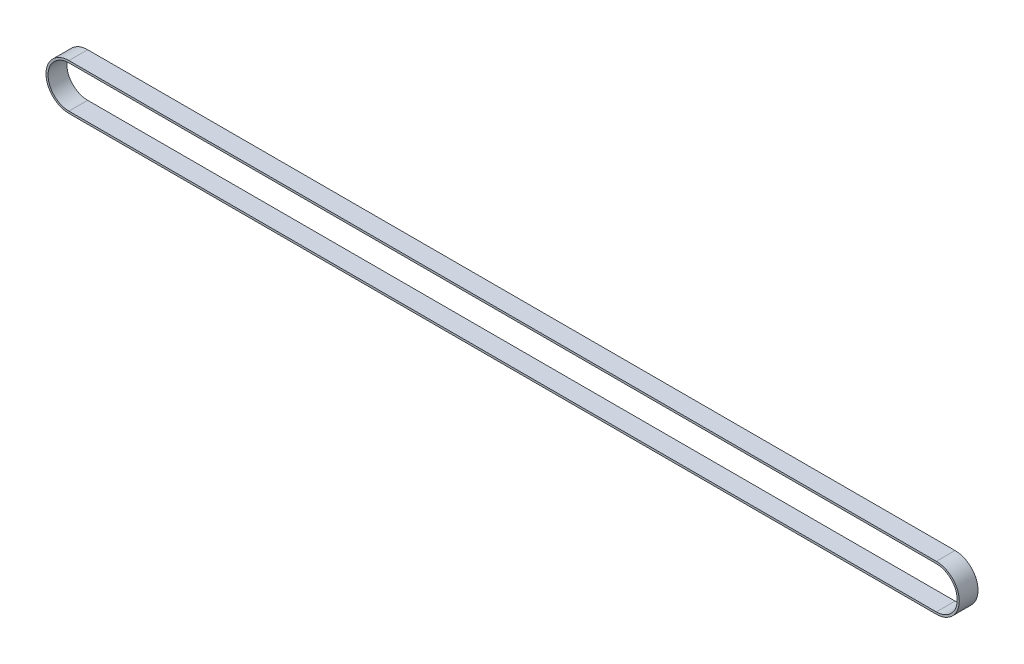
SolidWorks part; units mm, degrees
material "聚氨酯"
ref_plane "前视" through (0, 0, 0) normal (0, 0, 1) x (1, 0, 0)
ref_plane "上视" through (0, 0, 0) normal (0, 1, 0) x (1, 0, 0)
ref_plane "右视" through (0, 0, 0) normal (1, 0, 0) x (0, 0, -1)
sketch "草图2" plane through (0, 0, 0) normal (0, 0, 1) x (1, 0, 0)
  line L0 (0, 0) -> (1, 0) construction
  line L1 (0, 0) -> (0, 1) construction
  line L2 (-947.7489, 23.7599) -> (-21.7489, 23.7599)
  line L3 (-21.7489, -23.1901) -> (-947.7489, -23.1901)
  arc A0 (-947.7489, -23.1901) -> (-947.7489, 23.7599) centre (-947.7489, 0.2849) cw
  arc A1 (-21.7489, 23.7599) -> (-21.7489, -23.1901) centre (-21.7489, 0.2849) cw
extrude "拉伸-薄壁1" add sketch "草图2" against normal blind 20 from offset 1 thin thin type two direction wall 1 second wall 1.2 offset against normal yes
